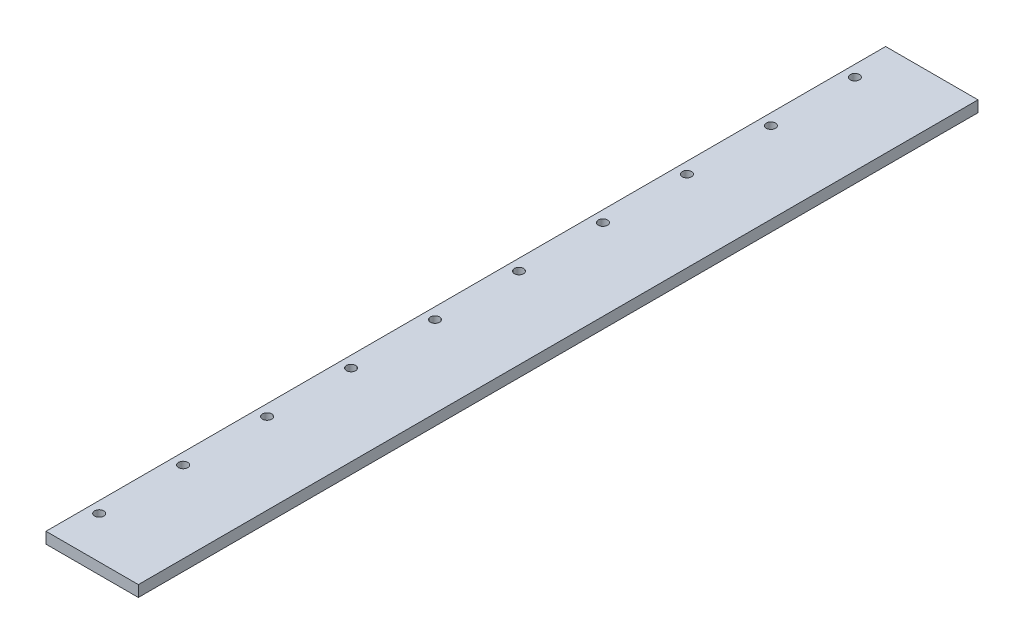
SolidWorks part; units mm, degrees
ref_plane "Front Plane" through (0, 0, 0) normal (0, 0, 1) x (1, 0, 0)
ref_plane "Top Plane" through (0, 0, 0) normal (0, 1, 0) x (1, 0, 0)
ref_plane "Right Plane" through (0, 0, 0) normal (1, 0, 0) x (0, 0, -1)
sketch "Sketch1" plane through (0, 0, 0) normal (0, 0, 1) x (1, 0, 0)
  line L1 (-16.5, -2) -> (16.5, -2)
  line L2 (-16.5, -2) -> (-16.5, 2)
  line L3 (-16.5, 2) -> (16.5, 2)
  line L4 (16.5, -2) -> (16.5, 2)
  line L5 (-16.5, -2) -> (16.5, 2) construction
  line L6 (-16.5, 2) -> (16.5, -2) construction
  point P0 (0, 0)
  dimension "D1" = 4
  dimension "D2" = 33
extrude "Boss-Extrude1" add sketch "Sketch1" along normal blind 300
sketch "Sketch2" plane through (0, 2, 0) normal (0, 1, 0) x (1, 0, 0)
  line L0 (-16.5, -300) -> (-16.5, 0) construction
  line L1 (16.5, 0) -> (-16.5, 0) construction
  point P0 (-12.5, -15)
  dimension "D1" = 4
  dimension "D2" = 15
hole_wizard "M4 Tapped Hole1" positions "3DSketch1" profile "Sketch3" tap size "M4" standard "DIN" end condition through all
sketch3d "3DSketch1"
  point P0 (-12.5, 2, 15)
sketch "Sketch3" plane through (-12.5, 2, 15) normal (1, 0, 0) x (0, 0, 1)
  line L0 (0, 0) -> (0, 4)
  line L1 (0, 4) -> (1.65, 4)
  line L2 (1.65, 4) -> (1.65, 0)
  line L5 (1.65, 0) -> (0, 0)
  line L11 (0, -6.35) -> (0, 107.95) construction
  dimension "Thru Tap Drill Dia." = 3.3
  dimension "Thru Tap Drill Depth" = 4
cosmetic thread "Hole Thread1" parameters "D2"=4
pattern_linear "LPattern1" count 10 spacing 30 along (0, 0, 1) of "M4 Tapped Hole1"
